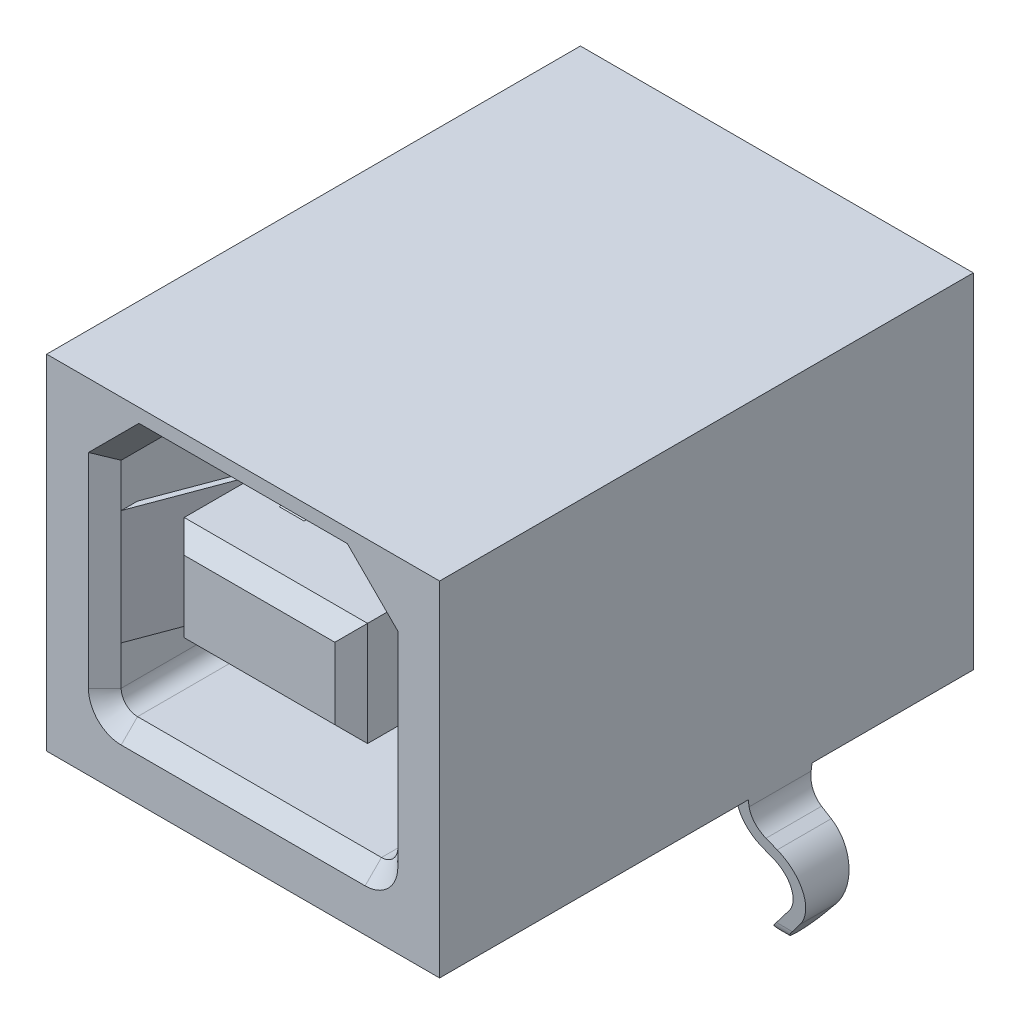
SolidWorks part; units mm, degrees
ref_plane "Front" through (0, 0, 0) normal (0, 0, 1) x (1, 0, 0)
ref_plane "Top" through (0, 0, 0) normal (0, 1, 0) x (1, 0, 0)
ref_plane "Right" through (0, 0, 0) normal (1, 0, 0) x (0, 0, -1)
sketch "Sketch1" plane through (0, 0, 0) normal (0, 0, 1) x (1, 0, 0)
  line L0 (-6, 5.25) -> (6, -5.25) construction
  line L1 (-6, 5.25) -> (6, 5.25)
  line L2 (-6, 5.25) -> (-6, -5.25)
  line L3 (-6, -5.25) -> (6, -5.25)
  line L4 (6, 5.25) -> (6, -5.25)
  dimension "D1" = 12
  dimension "D2" = 10.5
extrude "Base" add sketch "Sketch1" along normal mid plane 16.3
sketch "Sketch2" plane through (0, 0, 8.15) normal (0, 0, 1) x (1, 0, 0)
  line L0 (-2.975, 4.33) -> (-4.225, 3.08)
  line L1 (3.725, -3.45) -> (-3.725, -3.45)
  line L2 (4.225, -2.95) -> (4.225, 3.08)
  line L3 (2.975, 4.33) -> (-2.975, 4.33)
  line L4 (-4.225, -2.95) -> (-4.225, 3.08)
  line L5 (4.225, 3.08) -> (2.975, 4.33)
  line L6 (4.225, 4.33) -> (-4.225, -3.45) construction
  line L7 (6, 5.25) -> (-6, 5.25) construction
  line L9 (0, 0.44) -> (13.9883, 0.44) construction
  arc A0 (-3.725, -3.45) -> (-4.225, -2.95) centre (-3.725, -2.95) cw
  arc A1 (3.725, -3.45) -> (4.225, -2.95) centre (3.725, -2.95) ccw
  point P1 (4.225, 4.33)
  point P2 (-4.225, 4.33)
  point P12 (-4.225, -3.45)
  dimension "D1" = 0.5
  dimension "D2" = 4.81
  dimension "D3" = 8.45
  dimension "D5" = 7.78
extrude "Contact Opening" cut sketch "Sketch2" against normal blind 9
chamfer "Contact Opening Lead-in" distance 0.5 angle 45 8 edges at (-3.6, 3.705, 8.15) (0, 4.33, 8.15) (3.6, 3.705, 8.15) (4.225, 0.065, 8.15) (4.0786, -3.3036, 8.15) (0, -3.45, 8.15) (-4.0786, -3.3036, 8.15) (-4.225, 0.065, 8.15)
sketch "Sketch3" plane through (0, 0, -0.85) normal (0, 0, 1) x (1, 0, 0)
  line L0 (-2.8, 2.03) -> (2.8, -1.15) construction
  line L1 (-2.8, 2.03) -> (2.8, 2.03)
  line L2 (-2.8, 2.03) -> (-2.8, -1.15)
  line L3 (-2.8, -1.15) -> (2.8, -1.15)
  line L4 (2.8, 2.03) -> (2.8, -1.15)
  dimension "D1" = 5.6
  dimension "D2" = 3.18
extrude "Contact Area" add sketch "Sketch3" along normal blind 8.5
chamfer "Contact Area Lead-in" distance 0.5 angle 45 4 edges at (0, 2.03, 7.65) (2.8, 0.44, 7.65) (0, -1.15, 7.65) (-2.8, 0.44, 7.65)
ref_plane "Ground Leg Plane" through (0, 0, -2.25) normal (0, 0, 1) x (1, 0, 0)
sketch "Sketch4" plane through (0, 0, -2.25) normal (0, 0, 1) x (1, 0, 0)
  line L0 (0, 0) -> (0, -12.5407) construction
  line L1 (6.02, -5.058) -> (5.72, -5.1007)
  line L2 (6.4225, -5.35) -> (8.1, -5.35)
  line L3 (8.1, -5.35) -> (8.1, -5.65)
  line L5 (-6.1857, -5.65) -> (-8.1, -5.65)
  line L6 (-8.1, -5.35) -> (-8.1, -5.65)
  line L7 (-6.4225, -5.35) -> (-8.1, -5.35)
  line L8 (-6.02, -5.058) -> (-5.72, -5.1007)
  line L9 (6.1857, -5.65) -> (8.1, -5.65)
  arc A0 (6.02, -5.058) -> (6.4225, -5.35) centre (6.3271, -5.058) ccw
  arc A1 (-5.72, -5.1007) -> (-6.1857, -5.65) centre (-6.3271, -5.058) cw
  arc A2 (-6.02, -5.058) -> (-6.4225, -5.35) centre (-6.3271, -5.058) cw
  arc A5 (5.72, -5.1007) -> (6.1857, -5.65) centre (6.3271, -5.058) ccw
  dimension "D2" = 8.1
  dimension "D3" = 0.3
  dimension "D1" = 10.6
sketch "Sketch7" plane through (0, 0, 0) normal (0, 1, 0) x (1, 0, 0)
  line L0 (-4.225, -7.65) -> (-3.2152, -4.9513)
  line L1 (-3.3072, -2.6298) -> (-3.695, -1.8)
  line L2 (0, 0) -> (0, -8.8202) construction
  line L3 (-3.4657, -2.7039) -> (-3.8535, -1.8741)
  line L4 (-4.3889, -7.5887) -> (-3.3791, -4.89)
  line L5 (-3.695, -1.8) -> (-3.8535, -1.8741)
  line L6 (-4.225, -7.65) -> (-4.3889, -7.5887)
  line L7 (4.225, -7.65) -> (4.3889, -7.5887)
  line L8 (3.695, -1.8) -> (3.8535, -1.8741)
  line L9 (4.3889, -7.5887) -> (3.3791, -4.89)
  line L10 (3.4657, -2.7039) -> (3.8535, -1.8741)
  line L11 (3.3072, -2.6298) -> (3.695, -1.8)
  line L12 (4.225, -7.65) -> (3.2152, -4.9513)
  arc A0 (-3.2152, -4.9513) -> (-3.3072, -2.6298) centre (-6.025, -3.9) ccw
  arc A1 (-3.3791, -4.89) -> (-3.4657, -2.7039) centre (-6.025, -3.9) ccw
  arc A2 (3.3791, -4.89) -> (3.4657, -2.7039) centre (6.025, -3.9) cw
  arc A3 (3.2152, -4.9513) -> (3.3072, -2.6298) centre (6.025, -3.9) cw
  dimension "D2" = 3
  dimension "D5" = 3.75
  dimension "D1" = 5.85
  dimension "D3" = 1.8
  dimension "D4" = 0.53
  dimension "D6" = 0.175
extrude "Holding Tines" add sketch "Sketch7" along normal mid plane 3.5
ref_plane "Tail Plane" through (0, 0, -7.3) normal (0, 0, -1) x (-1, 0, 0)
ref_plane "Contact Plane" through (-1.25, 0, 0) normal (1, 0, 0) x (0, 0, -1)
ref_plane "SM TAILS PLANE" through (0.75, 0, 0) normal (1, 0, 0) x (0, 0, -1)
sketch "Sketch8" plane through (-1.25, 0, 0) normal (1, 0, 0) x (0, 0, -1)
  line L0 (0.85, 2.03) -> (-2.5953, 2.6783)
  line L1 (-4.3185, 2.4931) -> (-5.65, 1.93)
  line L2 (-7.15, 2.03) -> (0.85, 2.03) construction
  line L3 (0.85, 3.08) -> (0.85, -2.95) construction
  line L4 (-4.2503, 2.3319) -> (-5.5818, 1.7688)
  line L5 (0.8176, 1.858) -> (-2.6276, 2.5063)
  line L6 (0.8176, 1.858) -> (0.85, 2.03)
  line L7 (-5.5818, 1.7688) -> (-5.65, 1.93)
  line L8 (0.85, 2.03) -> (0.85, -1.15) construction
  line L9 (0.85, 0.44) -> (-6.7483, 0.44) construction
  line L10 (-5.5818, -0.8888) -> (-5.65, -1.05)
  line L11 (0.8176, -0.978) -> (0.85, -1.15)
  line L12 (0.8176, -0.978) -> (-2.6276, -1.6263)
  line L13 (-4.2503, -1.4519) -> (-5.5818, -0.8888)
  line L14 (-4.3185, -1.6131) -> (-5.65, -1.05)
  line L15 (0.85, -1.15) -> (-2.5953, -1.7983)
  arc A0 (-2.5953, 2.6783) -> (-4.3185, 2.4931) centre (-3.15, -0.27) ccw
  arc A1 (-2.6276, 2.5063) -> (-4.2503, 2.3319) centre (-3.15, -0.27) ccw
  arc A2 (-2.6276, -1.6263) -> (-4.2503, -1.4519) centre (-3.15, 1.15) cw
  arc A3 (-2.5953, -1.7983) -> (-4.3185, -1.6131) centre (-3.15, 1.15) cw
  dimension "D2" = 3
  dimension "D3" = 2.3
  dimension "D4" = 4
  dimension "D1" = 6.5
  dimension "D5" = 0.1
  dimension "D6" = 0.175
extrude "Contact" add sketch "Sketch8" along normal mid plane 0.75
pattern_linear "Contact Pattern" count 2 spacing 2.5 along (1, 0, 0) of "Contact"
sketch "Sketch12" plane through (0, -5.25, 0) normal (0, -1, 0) x (1, 0, 0)
  line L0 (0, 0) -> (0, 5.4435) construction
  line L1 (3.1821, 8.15) -> (4.725, 8.15) construction
  circle A0 centre (2.75, -0.85) radius 0.575
  circle A1 centre (-2.75, -0.85) radius 0.575
  point P5 (3.9536, 8.15)
  dimension "D1" = 1.15
  dimension "D2" = 2.75
  dimension "D3" = 9
sketch "Sketch13" plane through (0, 0, -2.25) normal (0, 0, 1) x (1, 0, 0)
  line L0 (6, -5.25) -> (6, -5.45)
  line L1 (6.4164, -6.1217) -> (6.736, -6.2805)
  line L2 (7.1575, -8.1791) -> (6.5272, -8.97)
  line L3 (6.8604, -7.9422) -> (6.23, -8.7332)
  line L4 (6.2473, -6.462) -> (6.567, -6.6208)
  line L5 (5.62, -5.25) -> (5.62, -5.45)
  line L6 (6.5272, -8.97) -> (6.23, -8.7332)
  line L7 (5.62, -5.25) -> (6, -5.25)
  line L8 (0, 0) -> (0, -9.739) construction
  line L9 (-6, -5.25) -> (6, -5.25) construction
  line L10 (6, -5.25) -> (6, 5.25) construction
  line L11 (-5.62, -5.25) -> (-6, -5.25)
  line L12 (-6.5272, -8.97) -> (-6.23, -8.7332)
  line L13 (-5.62, -5.25) -> (-5.62, -5.45)
  line L14 (-6.2473, -6.462) -> (-6.567, -6.6208)
  line L15 (-6.8604, -7.9422) -> (-6.23, -8.7332)
  line L16 (-7.1575, -8.1791) -> (-6.5272, -8.97)
  line L17 (-6.4164, -6.1217) -> (-6.736, -6.2805)
  line L18 (-6, -5.25) -> (-6, -5.45)
  arc A0 (6, -5.45) -> (6.4164, -6.1217) centre (6.75, -5.45) ccw
  arc A1 (6.736, -6.2805) -> (7.1575, -8.1791) centre (6.18, -7.4) cw
  arc A2 (6.567, -6.6208) -> (6.8604, -7.9422) centre (6.18, -7.4) cw
  arc A3 (5.62, -5.45) -> (6.2473, -6.462) centre (6.75, -5.45) ccw
  arc A4 (-5.62, -5.45) -> (-6.2473, -6.462) centre (-6.75, -5.45) cw
  arc A5 (-6.567, -6.6208) -> (-6.8604, -7.9422) centre (-6.18, -7.4) ccw
  arc A6 (-6.736, -6.2805) -> (-7.1575, -8.1791) centre (-6.18, -7.4) ccw
  arc A7 (-6, -5.45) -> (-6.4164, -6.1217) centre (-6.75, -5.45) cw
  dimension "D2" = 1.95
  dimension "D3" = 1.57
  dimension "D5" = 0.75
  dimension "D6" = 0.87
  dimension "D8" = 0.3472
  dimension "D1" = 0.2
  dimension "D4" = 0.38
  dimension "D7" = 0.18
extrude "TH Ground Legs" add sketch "Sketch13" along normal mid plane 1.95
sketch "Sketch14" plane through (0, 0, 0) normal (1, 0, 0) x (0, 0, -1)
  line L0 (3.225, -5.25) -> (3.225, -9)
  line L1 (2.7448, -8.5422) -> (3.225, -5.25)
  line L2 (3.225, -5.25) -> (8.15, -5.25) construction
  line L3 (1.7552, -8.5422) -> (1.275, -5.25)
  line L4 (1.275, -5.25) -> (1.275, -9)
  line L5 (3.225, -9) -> (1.275, -9)
  line L6 (2.25, -8.97) -> (2.25, -9.8721) construction
  line L7 (1.275, -8.97) -> (3.225, -8.97) construction
  arc A0 (1.7552, -8.5422) -> (2.7448, -8.5422) centre (2.25, -8.47) ccw
  point P1 (2.25, -9)
  dimension "D2" = 0.5
  dimension "D4" = 3.75
  dimension "D1" = 3.75
  dimension "D3" = 1.95
extrude "TH Ground Leg Shape" cut sketch "Sketch14" against normal through all and the other way through all
sketch "Sketch15" plane through (0, 0, -7.3) normal (0, 0, -1) x (-1, 0, 0)
  line L0 (-1.58, -5.25) -> (-0.92, -5.25)
  line L1 (-1.58, -5.25) -> (-1.58, -8.1)
  line L2 (-1.4588, -8.4) -> (-1.0412, -8.4)
  line L3 (-0.92, -5.25) -> (-0.92, -8.1)
  line L4 (-1.58, -8.1) -> (-1.4588, -8.4)
  line L5 (-0.92, -8.1) -> (-1.0412, -8.4)
  line L7 (0.92, -8.1) -> (1.0412, -8.4)
  line L8 (1.58, -8.1) -> (1.4588, -8.4)
  line L9 (0.92, -5.25) -> (0.92, -8.1)
  line L10 (1.4588, -8.4) -> (1.0412, -8.4)
  line L11 (1.58, -5.25) -> (1.58, -8.1)
  line L12 (1.58, -5.25) -> (0.92, -5.25)
  line L14 (0, 0) -> (0, -9.474) construction
  line L15 (6, -5.25) -> (-6, -5.25) construction
  dimension "D1" = 0.3
  dimension "D2" = 0.66
  dimension "D3" = 0.92
  dimension "D4" = 0.1212
  dimension "D5" = 3.15
  dimension "D6" = 0.1212
extrude "TH Tails" add sketch "Sketch15" along normal mid plane 0.25
pattern_linear "TH Tails Pattern" count 2 spacing 2 along (0, 0, 1) of "TH Tails"
